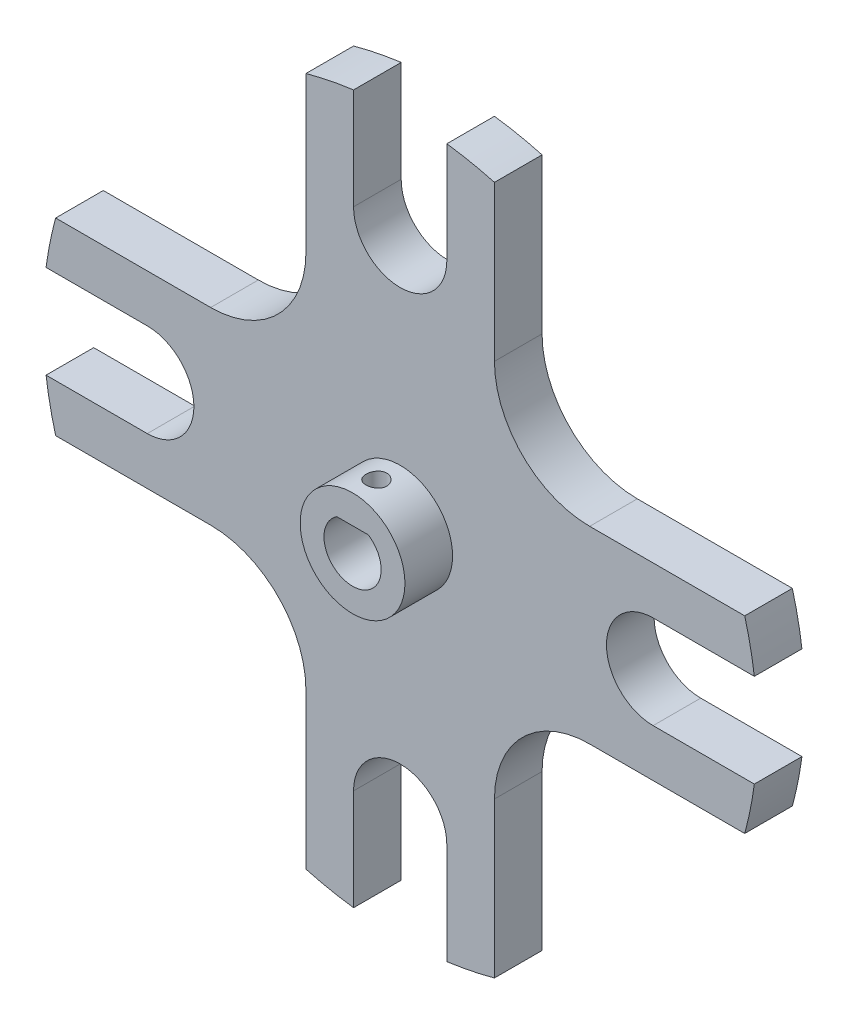
SolidWorks part; units mm, degrees
ref_plane "Plan de face" through (0, 0, 0) normal (0, 0, 1) x (1, 0, 0)
ref_plane "Plan de dessus" through (0, 0, 0) normal (0, 1, 0) x (1, 0, 0)
ref_plane "Plan de droite" through (0, 0, 0) normal (1, 0, 0) x (0, 0, -1)
sketch "Esquisse1" plane through (0, 0, 0) normal (0, 0, 1) x (1, 0, 0)
  circle A0 centre (0, 0) radius 75
  dimension "D1" = 150
extrude "Boss.-Extru.1" add sketch "Esquisse1" along normal mid plane 10 contours A0
sketch "Esquisse2" plane through (0, 0, 5) normal (0, 0, 1) x (1, 0, 0)
  line L0 (0, 74.996) -> (0, -78.8826) construction
  line L1 (-78.6495, 0) -> (78.0727, 0) construction
  line L2 (-79.2012, 9.7918) -> (77.5211, 9.7918) construction
  line L3 (78.0727, -9.7918) -> (-79.2012, -9.7918) construction
  line L4 (-53.106, 9.7918) -> (-53.106, -9.7918) construction
  line L5 (-53.106, 9.7918) -> (-74.3581, 9.7918)
  line L6 (-53.106, -9.7918) -> (-74.3581, -9.7918)
  arc A0 (-74.3581, 9.7918) -> (-74.3581, -9.7918) centre (0, 0) ccw
  arc A1 (-53.106, 9.7918) -> (-53.106, -9.7918) centre (-53.106, 0) cw
  arc A2 (0, -75) -> (0, 75) centre (0, 0) ccw
  dimension "D1" = 75
extrude "Enlèv. mat.-Extru.1" cut sketch "Esquisse2" against normal blind 20 contours L5 A0 L6 A1
pattern_circular "Répétition circulaire1" count 4 over 360 about axis through (0, 0, 0) along (0, 0, 1) of "Enlèv. mat.-Extru.1"
sketch "Esquisse3" plane through (0, 0, 5) normal (0, 0, 1) x (1, 0, 0)
  line L0 (-53.106, 9.7918) -> (-74.3581, 9.7918) construction
  line L1 (-19.7918, 72.3415) -> (-72.3415, 72.3415)
  line L2 (-19.7918, 72.3415) -> (-19.7918, 19.7918)
  line L3 (-19.7918, 19.7918) -> (-72.3415, 19.7918)
  line L4 (-72.3415, 72.3415) -> (-72.3415, 19.7918)
  line L5 (-9.7918, 53.106) -> (-9.7918, 74.3581) construction
  circle A0 centre (0, 0) radius 75 construction
  dimension "D1" = 10
  dimension "D2" = 10
extrude "Enlèv. mat.-Extru.2" cut sketch "Esquisse3" against normal blind 20 contours L2 L1 L4 L3
pattern_circular "Répétition circulaire2" count 4 over 360 about axis through (0, 0, 0) along (0, 0, 1) of "Enlèv. mat.-Extru.2"
fillet "Congé1" radius 20 4 edges at (19.7918, -19.7918, 0) (-19.7918, -19.7918, 0) (-19.7918, 19.7918, 0) (19.7918, 19.7918, 0)
sketch "Esquisse4" plane through (0, 0, 5) normal (0, 0, 1) x (1, 0, 0)
  line L0 (0, 5) -> (0, -6) construction
  line L1 (-3.3166, 5) -> (3.3166, 5)
  arc A0 (-3.3166, 5) -> (3.3166, 5) centre (0, 0) ccw
  dimension "D1" = 12
extrude "Enlèv. mat.-Extru.3" cut sketch "Esquisse4" against normal through all both and the other way through all
sketch "Esquisse6" plane through (0, 0, 5) normal (0, 0, 1) x (1, 0, 0)
  line L0 (-3.3166, 5) -> (3.3166, 5)
  arc A1 (-3.3166, 5) -> (3.3166, 5) centre (0, 0) ccw
  circle A2 centre (0, 0) radius 11
  dimension "D1" = 5
extrude "Boss.-Extru.2" add sketch "Esquisse6" along normal blind 10
sketch "Esquisse7" plane through (0, 0, 0) normal (0, 1, 0) x (1, 0, 0)
  line L0 (0, -15) -> (0, -5) construction
  line L1 (-11, -15) -> (11, -15) construction
  line L2 (-9.7918, -5) -> (9.7918, -5) construction
  circle A0 centre (0, -10) radius 2.175
  dimension "D1" = 4.35
extrude "Enlèv. mat.-Extru.4" cut sketch "Esquisse7" along normal blind 14
equation "\"Pitch Diameter\"= 150"
equation "\"Number of Teeth\"= 24"
equation "\"module\"= \"Pitch Diameter\" / \"Number of Teeth\""
equation "\"D1@Esquisse1\"=\"module\"*\"Number of Teeth\""
equation "\"D1@Esquisse2\"=\"Pitch Diameter\"/2"
